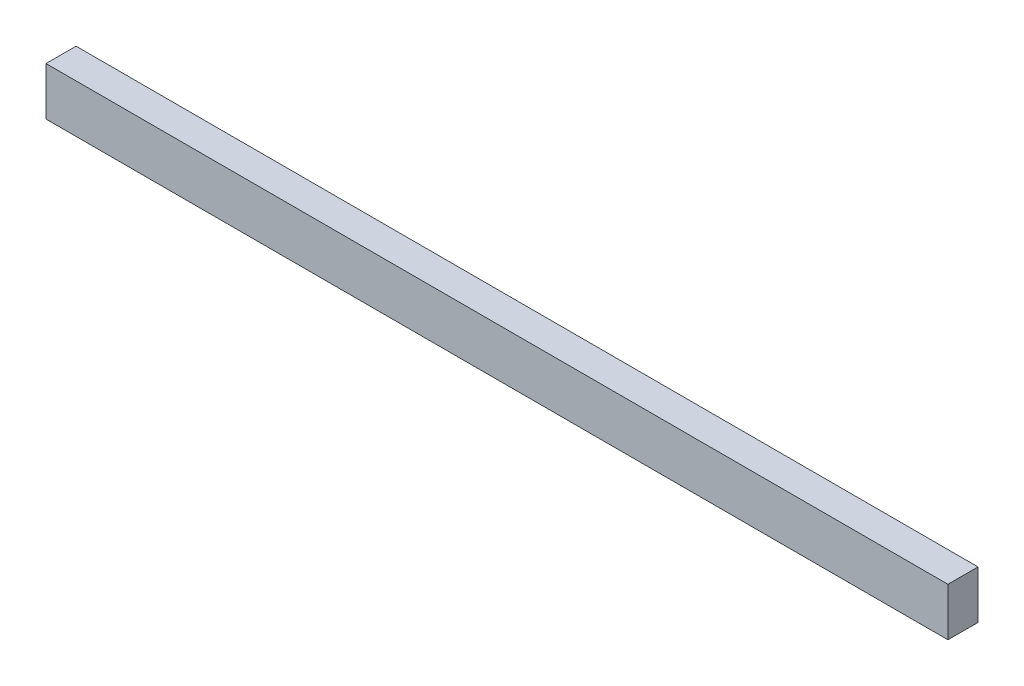
SolidWorks part; units mm, degrees
ref_plane "Plan de face" through (0, 0, 0) normal (0, 0, 1) x (1, 0, 0)
ref_plane "Plan de dessus" through (0, 0, 0) normal (0, 1, 0) x (1, 0, 0)
ref_plane "Plan de droite" through (0, 0, 0) normal (1, 0, 0) x (0, 0, -1)
sketch "Esquisse1" plane through (0, 0, 0) normal (0, 0, 1) x (1, 0, 0)
  line L1 (0, 0) -> (750, 0)
  line L2 (0, 0) -> (0, 40)
  line L3 (0, 40) -> (750, 40)
  line L4 (750, 0) -> (750, 40)
  dimension "D1" = 40
  dimension "D2" = 750
extrude "Boss.-Extru.1" add sketch "Esquisse1" along normal blind 25
